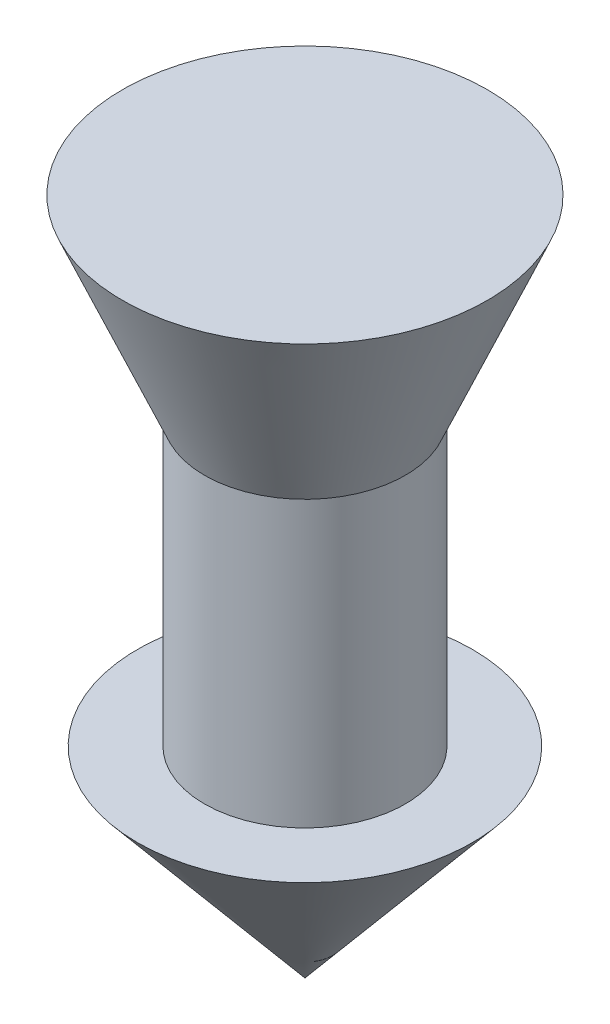
SolidWorks part; units mm, degrees
ref_plane "Front Plane" through (0, 0, 0) normal (0, 0, 1) x (1, 0, 0)
ref_plane "Top Plane" through (0, 0, 0) normal (0, 1, 0) x (1, 0, 0)
ref_plane "Right Plane" through (0, 0, 0) normal (1, 0, 0) x (0, 0, -1)
sketch "Sketch1" plane through (0, 0, 0) normal (1, 0, 0) x (0, 0, -1)
  line L1 (0, 0) -> (10, 12)
  line L2 (10, 12) -> (6, 12)
  line L3 (0, 0) -> (0, 40.5)
  line L4 (6, 12) -> (6, 29)
  line L5 (0, 40.5) -> (10.9, 40.5)
  line L6 (10.9, 40.5) -> (6, 29)
  point P9 (0, 0)
  dimension "D2" = 12
  dimension "D3" = 6
  dimension "D4" = 10.9
  dimension "D5" = 11.5
  dimension "D6" = 29
  dimension "D1" = 10
revolve "Revolve1" add sketch "Sketch1" angle 360 about L3
equation "\"D4@Sketch1\"=21.8/2"
